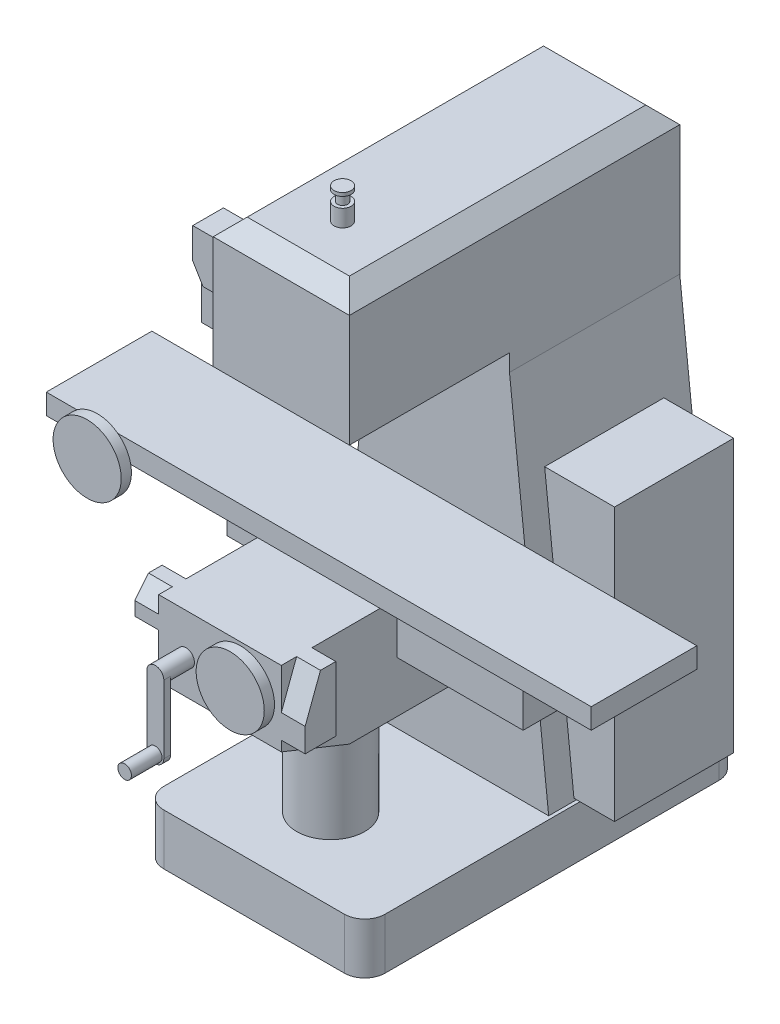
SolidWorks part; units mm, degrees
ref_plane "正面" through (0, 0, 0) normal (0, 0, 1) x (1, 0, 0)
ref_plane "平面" through (0, 0, 0) normal (0, 1, 0) x (1, 0, 0)
ref_plane "右側面" through (0, 0, 0) normal (1, 0, 0) x (0, 0, -1)
sketch "ｽｹｯﾁ2" plane through (0, 0, 0) normal (0, 0, 1) x (1, 0, 0)
  line L1 (-63.3234, 86.9012) -> (336.6766, 86.9012)
  line L2 (-63.3234, 86.9012) -> (-63.3234, -343.0988)
  line L3 (-63.3234, -343.0988) -> (336.6766, -343.0988)
  line L4 (336.6766, 86.9012) -> (336.6766, -343.0988)
  dimension "D1" = 400
  dimension "D2" = 430
extrude "ﾎﾞｽ - 押し出し2" add sketch "ｽｹｯﾁ2" along normal blind 970
sketch "ｽｹｯﾁ3" plane through (0, 0, 0) normal (0, 0, -1) x (-1, 0, 0)
  line L0 (-336.6766, -343.0988) -> (-451.6766, -1413.0988)
  line L1 (-451.6766, -1413.0988) -> (178.3234, -1413.0988)
  line L2 (178.3234, -1413.0988) -> (63.3234, -343.0988)
  line L3 (63.3234, -343.0988) -> (-336.6766, -343.0988)
  line L4 (-336.6766, -343.0988) -> (-337.1774, -342.9948)
  line L5 (-336.6766, 86.9012) -> (63.3234, 86.9012) construction
  line M4 (-336.6766, -343.0988) -> (63.3234, -343.0988)
  dimension "D1" = 630
  dimension "1600" = 1500
  dimension "D3" = 115
extrude "ﾎﾞｽ - 押し出し3" add sketch "ｽｹｯﾁ3" against normal blind 500 contours L1 L2 L0 M4
sketch "ｽｹｯﾁ4" plane through (0, -1413.0988, 0) normal (0, -1, 0) x (-1, 0, 0)
  line L1 (-461.6766, 50) -> (188.3234, 50)
  line L2 (-461.6766, 50) -> (-461.6766, -1050)
  line L3 (-461.6766, -1050) -> (188.3234, -1050)
  line L4 (188.3234, 50) -> (188.3234, -1050)
  line L5 (-451.6766, 0) -> (178.3234, 0) construction
  line L7 (178.3234, -500) -> (178.3234, 0) construction
  dimension "D1" = 1100
  dimension "D2" = 650
  dimension "D3" = 10
  dimension "D4" = 50
extrude "ﾎﾞｽ - 押し出し4" add sketch "ｽｹｯﾁ4" along normal blind 150
sketch "ｽｹｯﾁ5" plane through (0, 86.9012, 0) normal (0, 1, 0) x (1, 0, 0)
  line L0 (336.6766, -970) -> (-63.3234, -970) construction
  line L1 (336.6766, -970) -> (336.6766, 0) construction
  circle A0 centre (136.6766, -790) radius 25
  dimension "D1" = 50
  dimension "D2" = 180
  dimension "D3" = 200
extrude "ﾎﾞｽ - 押し出し5" add sketch "ｽｹｯﾁ5" along normal blind 50
sketch "ｽｹｯﾁ6" plane through (0, 136.9012, 0) normal (0, 1, 0) x (1, 0, 0)
  circle A0 centre (136.6766, -790) radius 15
  circle A1 centre (136.6766, -790) radius 25 construction
  dimension "D1" = 30
extrude "ﾎﾞｽ - 押し出し6" add sketch "ｽｹｯﾁ6" along normal blind 30
sketch "ｽｹｯﾁ7" plane through (0, 166.9012, 0) normal (0, 1, 0) x (1, 0, 0)
  circle A0 centre (136.6766, -790) radius 25
  circle A1 centre (136.6766, -790) radius 15 construction
  dimension "D1" = 50
extrude "ﾎﾞｽ - 押し出し7" add sketch "ｽｹｯﾁ7" along normal blind 10
chamfer "面取り1" distance 50 angle 45 7 edges at (-63.3234, 86.9012, 485) (136.6766, 86.9012, 0) (136.6766, 86.9012, 970) (336.6766, 86.9012, 485) (136.6766, -343.0988, 970)
sketch "ｽｹｯﾁ8" plane through (0, -343.0988, 0) normal (0, -1, 0) x (-1, 0, 0)
  line L0 (-336.6766, -1600) -> (-336.6766, -970) construction
  line L1 (63.3234, -970) -> (-336.6766, -970) construction
  circle A0 centre (-136.6766, -790) radius 55
  dimension "D3" = 110
  dimension "D1" = 200
  dimension "D2" = 180
extrude "ﾎﾞｽ - 押し出し8" add sketch "ｽｹｯﾁ8" along normal blind 20
sketch "ｽｹｯﾁ9" plane through (0, -363.0988, 0) normal (0, -1, 0) x (-1, 0, 0)
  circle A0 centre (-136.6766, -790) radius 50
  circle A1 centre (-136.6766, -790) radius 55 construction
  dimension "D1" = 100
extrude "ﾎﾞｽ - 押し出し9" add sketch "ｽｹｯﾁ9" along normal blind 40
chamfer "面取り2" distance 15 angle 45 1 edges at (136.6766, -403.0988, 740)
sketch "ｽｹｯﾁ10" plane through (0, -403.0988, 0) normal (0, -1, 0) x (-1, 0, 0)
  circle A0 centre (-136.6766, -790) radius 10
  circle A1 centre (-136.6766, -790) radius 35 construction
  dimension "D1" = 20
extrude "ﾎﾞｽ - 押し出し10" add sketch "ｽｹｯﾁ10" along normal blind 50
sketch "ｽｹｯﾁ11" plane through (0, 0, 500) normal (0, 0, 1) x (1, 0, 0)
  line L1 (-33.3234, -763.0988) -> (326.6766, -763.0988)
  line L2 (-33.3234, -763.0988) -> (-33.3234, -1063.0988)
  line L3 (-33.3234, -1063.0988) -> (326.6766, -1063.0988)
  line L4 (326.6766, -763.0988) -> (326.6766, -1063.0988)
  line L6 (451.6766, -1413.0988) -> (-178.3234, -1413.0988) construction
  line L9 (461.6766, -1563.0988) -> (461.6766, -1413.0988) construction
  dimension "D1" = 135
  dimension "800" = 360
  dimension "D3" = 350
  dimension "D4" = 300
extrude "ﾎﾞｽ - 押し出し11" add sketch "ｽｹｯﾁ11" along normal blind 660
sketch "ｽｹｯﾁ12" plane through (0, -763.0988, 0) normal (0, 1, 0) x (1, 0, 0)
  line L0 (-33.3234, -1160) -> (-33.3234, -500) construction
  line L1 (-653.3234, -560) -> (946.6766, -560)
  line L2 (-653.3234, -560) -> (-653.3234, -870)
  line L3 (-653.3234, -870) -> (946.6766, -870)
  line L4 (946.6766, -560) -> (946.6766, -870)
  line L6 (326.6766, -1160) -> (-33.3234, -1160) construction
  dimension "D1" = 310
  dimension "D2" = 1600
  dimension "D3" = 620
  dimension "D4" = 600
extrude "ﾎﾞｽ - 押し出し12" add sketch "ｽｹｯﾁ12" along normal blind 60
sketch "ｽｹｯﾁ13" plane through (0, 0, 0) normal (1, 0, 0) x (0, 0, -1)
  line L0 (-500, -343.0988) -> (-500, -1413.0988) construction
  line L1 (-425, -606.1423) -> (-75, -606.1423)
  line L2 (-425, -606.1423) -> (-425, -1406.1423)
  line L3 (-425, -1406.1423) -> (-75, -1406.1423)
  line L4 (-75, -606.1423) -> (-75, -1406.1423)
  line L5 (-500, -1506.1423) -> (0, -1506.1423) construction
  dimension "D1" = 350
  dimension "D2" = 75
  dimension "D3" = 800
  dimension "D4" = 100
extrude "ﾎﾞｽ - 押し出し13" add sketch "ｽｹｯﾁ13" along normal blind 570
sketch "ｽｹｯﾁ14" plane through (0, -1413.0988, 0) normal (0, 1, 0) x (1, 0, 0)
  line L0 (461.6766, -1050) -> (-188.3234, -1050) construction
  line L1 (-188.3234, -1050) -> (-188.3234, 50) construction
  circle A0 centre (121.6766, -810) radius 100
  dimension "D1" = 200
  dimension "D2" = 240
  dimension "D3" = 310
extrude "ﾎﾞｽ - 押し出し14" add sketch "ｽｹｯﾁ14" along normal blind 400
sketch "ｽｹｯﾁ15" plane through (0, 0, 970) normal (0, 0, 1) x (1, 0, 0)
  line L0 (-63.3234, 25.3339) -> (-133.3234, 25.3339)
  line L1 (-63.3234, 36.9012) -> (-63.3234, -293.0988) construction
  line L2 (-133.3234, 25.3339) -> (-133.3234, -64.6661)
  line L3 (-133.3234, -64.6661) -> (-103.3234, -114.6661)
  line L4 (-103.3234, -114.6661) -> (-63.3234, -114.6661)
  line L5 (-63.3234, -114.6661) -> (-63.3234, 25.3339)
  dimension "D1" = 70
  dimension "D2" = 140
  dimension "D3" = 90
  dimension "D4" = 40
extrude "ﾎﾞｽ - 押し出し15" add sketch "ｽｹｯﾁ15" against normal blind 100
sketch "ｽｹｯﾁ16" plane through (0, 0, 970) normal (0, 0, 1) x (1, 0, 0)
  line L0 (-63.3234, 25.3339) -> (-133.3234, 25.3339)
  line L1 (-133.3234, 25.3339) -> (-133.3234, -64.6661)
  line L2 (-133.3234, -64.6661) -> (-103.3234, -114.6661)
  line L3 (-103.3234, -114.6661) -> (-63.3234, -114.6661)
  line L4 (-63.3234, -114.6661) -> (-63.3234, 25.3339)
extrude "ｶｯﾄ - 押し出し1" cut sketch "ｽｹｯﾁ16" against normal blind 10
sketch "ｽｹｯﾁ17" plane through (0, 0, 870) normal (0, 0, 1) x (1, 0, 0)
  line L0 (-653.3234, -703.0988) -> (946.6766, -703.0988) construction
  line L1 (-653.3234, -703.0988) -> (-653.3234, -763.0988) construction
  circle A0 centre (-503.3234, -783.0988) radius 100
  dimension "D1" = 200
  dimension "D2" = 80
  dimension "D3" = 150
extrude "ﾎﾞｽ - 押し出し16" add sketch "ｽｹｯﾁ17" along normal blind 30
sketch "ｽｹｯﾁ18" plane through (-33.3234, 0, 0) normal (-1, 0, 0) x (0, 0, 1)
  line L0 (1160, -1063.0988) -> (1160, -983.0988)
  line L1 (1160, -763.0988) -> (1160, -1063.0988) construction
  line L2 (1160, -983.0988) -> (960, -1063.0988)
  line L3 (1160, -1063.0988) -> (500, -1063.0988) construction
  line L4 (960, -1063.0988) -> (1160, -1063.0988)
  dimension "20" = 200
  dimension "D2" = 80
extrude "ｶｯﾄ - 押し出し2" cut sketch "ｽｹｯﾁ18" against normal up to next
sketch "ｽｹｯﾁ19" plane through (0, -763.0988, 0) normal (0, -1, 0) x (-1, 0, 0)
  line L0 (-326.6766, -870) -> (-326.6766, -560) construction
  line L1 (-326.6766, -820) -> (-696.6766, -820)
  line L2 (-326.6766, -820) -> (-326.6766, -610)
  line L3 (-326.6766, -610) -> (-696.6766, -610)
  line L4 (-696.6766, -820) -> (-696.6766, -610)
  line L5 (-326.6766, -870) -> (-946.6766, -870) construction
  line L6 (-946.6766, -560) -> (-326.6766, -560) construction
  line L7 (-946.6766, -870) -> (-946.6766, -560) construction
  dimension "D1" = 50
  dimension "D2" = 50
  dimension "200" = 250
extrude "ﾎﾞｽ - 押し出し17" add sketch "ｽｹｯﾁ19" along normal blind 150
sketch "ｽｹｯﾁ20" plane through (0, -763.0988, 0) normal (0, -1, 0) x (-1, 0, 0)
  line L0 (33.3234, -870) -> (33.3234, -560) construction
  line L1 (33.3234, -810) -> (183.3234, -810)
  line L2 (33.3234, -810) -> (33.3234, -610)
  line L3 (33.3234, -610) -> (183.3234, -610)
  line L4 (183.3234, -810) -> (183.3234, -610)
  line L5 (33.3234, -560) -> (653.3234, -560) construction
  dimension "D1" = 150
  dimension "D2" = 200
  dimension "D3" = 50
extrude "ﾎﾞｽ - 押し出し18" add sketch "ｽｹｯﾁ20" along normal blind 100
sketch "ｽｹｯﾁ21" plane through (0, 0, 1160) normal (0, 0, 1) x (1, 0, 0)
  line L0 (-33.3234, -763.0988) -> (-33.3234, -983.0988) construction
  line L1 (326.6766, -763.0988) -> (-33.3234, -763.0988) construction
  circle A0 centre (46.6766, -883.0988) radius 25
  dimension "D1" = 50
  dimension "D2" = 80
  dimension "D3" = 120
extrude "ﾎﾞｽ - 押し出し19" add sketch "ｽｹｯﾁ21" along normal blind 70
sketch "ｽｹｯﾁ22" plane through (0, 0, 1160) normal (0, 0, 1) x (1, 0, 0)
  line L0 (326.6766, -763.0988) -> (-33.3234, -763.0988) construction
  line L1 (326.6766, -983.0988) -> (326.6766, -763.0988) construction
  circle A0 centre (206.6766, -873.0988) radius 100
  point P2 (146.6766, -763.0988)
  dimension "D1" = 200
  dimension "D2" = 110
  dimension "D3" = 120
extrude "ﾎﾞｽ - 押し出し20" add sketch "ｽｹｯﾁ22" along normal blind 30
sketch "ｽｹｯﾁ23" plane through (0, 0, 1230) normal (0, 0, 1) x (1, 0, 0)
  line L2 (21.6766, -883.0988) -> (21.6766, -1083.0988)
  line L4 (71.6766, -883.0988) -> (71.6766, -1083.0988)
  circle A0 centre (46.6766, -883.0988) radius 25 construction
  arc A1 (21.6766, -883.0988) -> (71.6766, -883.0988) centre (46.6766, -883.0988) cw
  circle A2 centre (46.6766, -883.0988) radius 25 construction
  arc A3 (21.6766, -1083.0988) -> (71.6766, -1083.0988) centre (46.6766, -1083.0988) ccw
  dimension "D1" = 50
  dimension "D2" = 200
extrude "ﾎﾞｽ - 押し出し21" add sketch "ｽｹｯﾁ23" along normal blind 20
sketch "ｽｹｯﾁ24" plane through (0, 0, 1250) normal (0, 0, 1) x (1, 0, 0)
  circle A0 centre (46.6766, -1083.0988) radius 20
  arc A1 (21.6766, -1083.0988) -> (71.6766, -1083.0988) centre (46.6766, -1083.0988) ccw construction
  dimension "D1" = 40
extrude "ﾎﾞｽ - 押し出し22" add sketch "ｽｹｯﾁ24" along normal blind 90
sketch "ｽｹｯﾁ25" plane through (-33.3234, 0, 0) normal (-1, 0, 0) x (0, 0, 1)
  line L1 (1160, -763.0988) -> (1080, -763.0988)
  line L2 (1160, -763.0988) -> (1160, -853.0988)
  line L3 (1160, -853.0988) -> (1080, -853.0988)
  line L4 (1080, -763.0988) -> (1080, -853.0988)
  dimension "D1" = 80
  dimension "D2" = 90
extrude "ﾎﾞｽ - 押し出し23" add sketch "ｽｹｯﾁ25" along normal blind 70
sketch "ｽｹｯﾁ26" plane through (-103.3234, 0, 0) normal (-1, 0, 0) x (0, 0, 1)
  line L0 (1160, -763.0988) -> (1120, -763.0988)
  line L1 (1160, -763.0988) -> (1080, -763.0988) construction
  line L2 (1120, -763.0988) -> (1160, -813.0988)
  line L3 (1160, -853.0988) -> (1160, -763.0988) construction
  line L4 (1160, -813.0988) -> (1160, -763.0988)
  dimension "D1" = 40
  dimension "D2" = 50
extrude "ｶｯﾄ - 押し出し3" cut sketch "ｽｹｯﾁ26" against normal blind 70
sketch "ｽｹｯﾁ27" plane through (326.6766, 0, 0) normal (1, 0, 0) x (0, 0, -1)
  line L1 (-1160, -763.0988) -> (-1070, -763.0988)
  line L2 (-1160, -763.0988) -> (-1160, -953.0988)
  line L3 (-1160, -953.0988) -> (-1070, -953.0988)
  line L4 (-1070, -763.0988) -> (-1070, -953.0988)
  dimension "D1" = 90
  dimension "D2" = 190
extrude "ﾎﾞｽ - 押し出し24" add sketch "ｽｹｯﾁ27" along normal blind 70
sketch "ｽｹｯﾁ28" plane through (396.6766, 0, 0) normal (1, 0, 0) x (0, 0, -1)
  line L0 (-1115, -763.0988) -> (-1160, -883.0988)
  line L1 (-1070, -763.0988) -> (-1160, -763.0988) construction
  line L2 (-1160, -763.0988) -> (-1160, -953.0988) construction
  line L3 (-1160, -883.0988) -> (-1160, -763.0988)
  line L4 (-1160, -763.0988) -> (-1115, -763.0988)
  dimension "D2" = 120
extrude "ｶｯﾄ - 押し出し4" cut sketch "ｽｹｯﾁ28" against normal blind 70
fillet "ﾌｨﾚｯﾄ1" radius 60 4 edges at (-188.3234, -1488.0988, -50) (461.6766, -1488.0988, -50) (-188.3234, -1488.0988, 1050) (461.6766, -1488.0988, 1050)
sketch "ｽｹｯﾁ29" plane through (-63.3234, 0, 0) normal (-1, 0, 0) x (0, 0, 1)
  line L0 (500, -343.0988) -> (0, -343.0988) construction
  line L1 (420, -363.0988) -> (470, -363.0988)
  line L2 (420, -363.0988) -> (420, -413.0988)
  line L3 (420, -413.0988) -> (470, -413.0988)
  line L4 (470, -363.0988) -> (470, -413.0988)
  line L5 (500, -1413.0988) -> (500, -343.0988) construction
  dimension "D1" = 50
  dimension "D2" = 50
  dimension "D3" = 20
  dimension "D4" = 30
extrude "ﾎﾞｽ - 押し出し25" add sketch "ｽｹｯﾁ29" along normal blind 200
sketch "ｽｹｯﾁ30" plane through (0, 0, 470) normal (0, 0, 1) x (1, 0, 0)
  line L0 (-263.3234, -413.0988) -> (-70.8467, -413.0988) construction
  line L1 (-263.3234, -363.0988) -> (-213.3234, -363.0988)
  line L2 (-263.3234, -363.0988) -> (-263.3234, -413.0988)
  line L3 (-263.3234, -413.0988) -> (-213.3234, -413.0988)
  line L4 (-213.3234, -363.0988) -> (-213.3234, -413.0988)
  dimension "D1" = 50
extrude "ﾎﾞｽ - 押し出し26" add sketch "ｽｹｯﾁ30" along normal blind 150
sketch "ｽｹｯﾁ31" plane through (0, 0, 620) normal (0, 0, 1) x (1, 0, 0)
  line L0 (-213.3234, -363.0988) -> (-263.3234, -363.0988) construction
  line L1 (-368.3234, -308.0988) -> (-108.3234, -308.0988)
  line L2 (-368.3234, -308.0988) -> (-368.3234, -468.0988)
  line L3 (-368.3234, -468.0988) -> (-108.3234, -468.0988)
  line L4 (-108.3234, -308.0988) -> (-108.3234, -468.0988)
  line L5 (-263.3234, -363.0988) -> (-263.3234, -413.0988) construction
  dimension "D1" = 260
  dimension "D2" = 160
  dimension "D3" = 55
  dimension "D4" = 105
extrude "ﾎﾞｽ - 押し出し27" add sketch "ｽｹｯﾁ31" along normal blind 80
